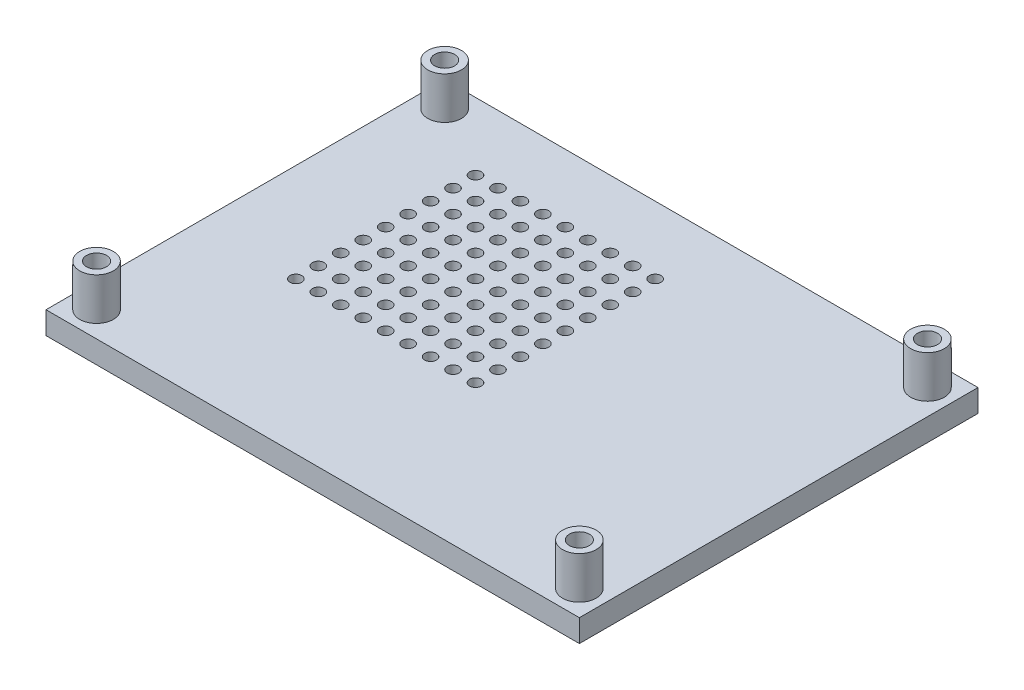
SolidWorks part; units mm, degrees
ref_plane "Front Plane" through (0, 0, 0) normal (0, 0, 1) x (1, 0, 0)
ref_plane "Top Plane" through (0, 0, 0) normal (0, 1, 0) x (1, 0, 0)
ref_plane "Right Plane" through (0, 0, 0) normal (1, 0, 0) x (0, 0, -1)
sketch "Sketch1" plane through (0, 0, 0) normal (0, 1, 0) x (1, 0, 0)
  line L1 (-43.3314, -35.4977) -> (51.6686, -35.4977)
  line L2 (-43.3314, -35.4977) -> (-43.3314, 35.5023)
  line L3 (-43.3314, 35.5023) -> (51.6686, 35.5023)
  line L4 (51.6686, -35.4977) -> (51.6686, 35.5023)
  dimension "D1" = 95
  dimension "D2" = 71
extrude "Boss-Extrude1" add sketch "Sketch1" along normal blind 4
sketch "Sketch2" plane through (0, 4, 0) normal (0, 1, 0) x (1, 0, 0)
  line L0 (-38.8314, -30.9977) -> (-38.8314, 31.0023) construction
  line L1 (-38.8314, 31.0023) -> (47.1686, 31.0023) construction
  line L2 (47.1686, 31.0023) -> (47.1686, -30.9977) construction
  line L3 (47.1686, -30.9977) -> (-38.8314, -30.9977) construction
  line L4 (-43.3314, 35.5023) -> (-43.3314, -35.4977) construction
  line L5 (51.6686, -35.4977) -> (51.6686, 35.5023) construction
  line L6 (-43.3314, -35.4977) -> (51.6686, -35.4977) construction
  line L7 (51.6686, 35.5023) -> (-43.3314, 35.5023) construction
  circle A0 centre (-38.8314, -30.9977) radius 3
  circle A1 centre (-38.8314, 31.0023) radius 3
  circle A2 centre (47.1686, 31.0023) radius 3
  circle A3 centre (47.1686, -30.9977) radius 3
  dimension "D5" = 6
  dimension "D1" = 4.5
  dimension "D2" = 4.5
  dimension "D3" = 4.5
  dimension "D4" = 4.5
extrude "Boss-Extrude2" add sketch "Sketch2" along normal blind 7.5
sketch "Sketch3" plane through (0, 11.5, 0) normal (0, 1, 0) x (1, 0, 0)
  circle A0 centre (-38.8314, 31.0023) radius 1.775
  circle A1 centre (-38.8314, -30.9977) radius 1.775
  circle A2 centre (47.1686, -30.9977) radius 1.775
  circle A3 centre (47.1686, 31.0023) radius 1.775
  circle A4 centre (-38.8314, 31.0023) radius 3 construction
  circle A5 centre (-38.8314, -30.9977) radius 3 construction
  circle A6 centre (47.1686, -30.9977) radius 3 construction
  circle A7 centre (47.1686, 31.0023) radius 3 construction
  dimension "D1" = 3.55
extrude "Cut-Extrude1" cut sketch "Sketch3" against normal through all
sketch "Sketch4" plane through (0, 4, 0) normal (0, 1, 0) x (1, 0, 0)
  line L0 (-25.8314, 23.5023) -> (6.1686, 23.5023) construction
  line L1 (-25.8314, 23.5023) -> (-25.8314, -8.4977) construction
  line L2 (-43.3314, 35.5023) -> (-43.3314, -35.4977) construction
  line L3 (51.6686, 35.5023) -> (-43.3314, 35.5023) construction
  circle A0 centre (-25.8314, 23.5023) radius 1.05
  dimension "D1" = 2.1
  dimension "D2" = 32
  dimension "D3" = 32
  dimension "D4" = 17.5
  dimension "D5" = 12
extrude "Cut-Extrude2" cut sketch "Sketch4" against normal through all
pattern_linear "LPattern1" count 9 spacing 4 along (1, 0, 0) count 9 spacing 4 along (0, 0, 1) of "Cut-Extrude2"
